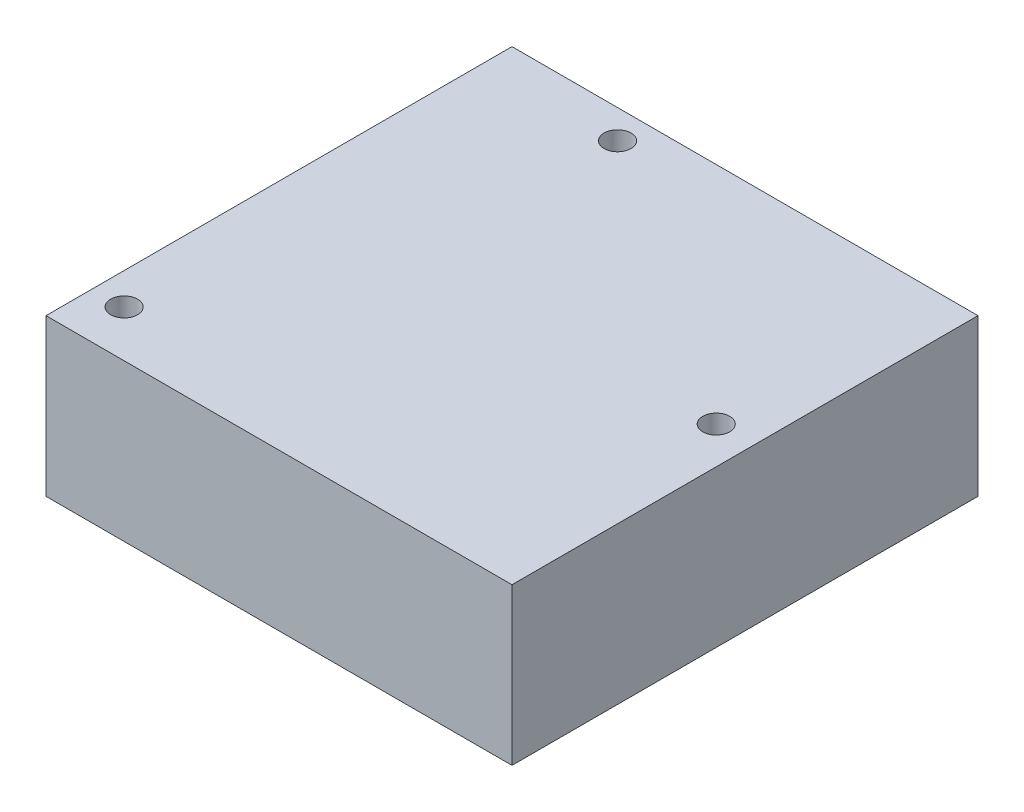
SolidWorks part; units mm, degrees
material "1060 Alloy"
ref_plane "Front Plane" through (0, 0, 0) normal (0, 0, 1) x (1, 0, 0)
ref_plane "Top Plane" through (0, 0, 0) normal (0, 1, 0) x (1, 0, 0)
ref_plane "Right Plane" through (0, 0, 0) normal (1, 0, 0) x (0, 0, -1)
sketch "Sketch1" plane through (0, 0, 0) normal (0, 1, 0) x (1, 0, 0)
  line L1 (21.59, 21.59) -> (-21.59, 21.59)
  line L2 (21.59, 21.59) -> (21.59, -21.59)
  line L3 (21.59, -21.59) -> (-21.59, -21.59)
  line L4 (-21.59, 21.59) -> (-21.59, -21.59)
  line L5 (21.59, 21.59) -> (-21.59, -21.59) construction
  line L6 (21.59, -21.59) -> (-21.59, 21.59) construction
  point P0 (0, 0)
  dimension "D1" = 43.18
  dimension "D2" = 43.18
extrude "Boss-Extrude1" add sketch "Sketch1" along normal blind 15 contours L4 L3 L2 L1
hole_wizard "M3x0.5 Tapped Hole1" positions "Sketch3" profile "Sketch2" tap size "M3x0.5" standard "ANSI Metric" end condition through all
sketch "Sketch3" plane through (0, 15, 0) normal (0, 1, 0) x (1, 0, 0)
  line L0 (-21.59, 21.59) -> (-21.59, -21.59) construction
  line L1 (21.59, -21.59) -> (-21.59, -21.59) construction
  point P0 (-18.669, -17.272)
  point P2 (-9.144, 18.923)
  point P4 (18.161, 0.762)
  dimension "D1" = 2.921
  dimension "D2" = 4.318
  dimension "D3" = 12.446
  dimension "D4" = 40.513
  dimension "D5" = 39.751
  dimension "D6" = 22.352
sketch "Sketch2" plane through (-18.669, 15, 17.272) normal (1, 0, 0) x (0, 0, 1)
  line L0 (0, 0) -> (0, 15)
  line L1 (0, 15) -> (1.25, 15)
  line L2 (1.25, 15) -> (1.25, 0)
  line L5 (1.25, 0) -> (0, 0)
  line L11 (0, -6.35) -> (0, 107.95) construction
  dimension "Thru Tap Drill Dia." = 2.5
  dimension "Thru Tap Drill Depth" = 15
cosmetic thread "Hole Thread1" parameters "D2"=3
cosmetic thread "Hole Thread2" parameters "D2"=3
cosmetic thread "Hole Thread3" parameters "D2"=3
chamfer "Chamfer1" distance 0.5 angle 45 4 edges at (0, 0, 21.59) (-21.59, 0, 0) (21.59, 0, 0) (0, 0, -21.59)
